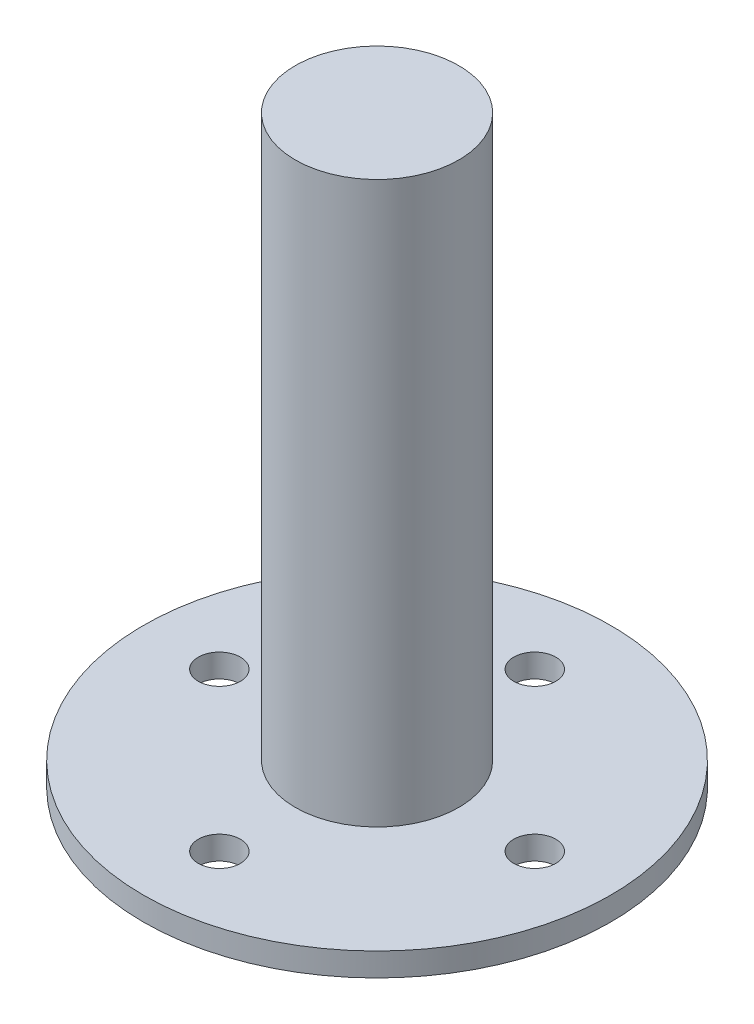
SolidWorks part; units mm, degrees
ref_plane "Płaszczyzna przednia" through (0, 0, 0) normal (0, 0, 1) x (1, 0, 0)
ref_plane "Płaszczyzna górna" through (0, 0, 0) normal (0, 1, 0) x (1, 0, 0)
ref_plane "Płaszczyzna prawa" through (0, 0, 0) normal (1, 0, 0) x (0, 0, -1)
sketch "Szkic1" plane through (0, 0, 0) normal (0, 1, 0) x (1, 0, 0)
  circle A0 centre (0, 0) radius 50
  dimension "D1" = 100
extrude "Dodanie-wyciągnięcie1" add sketch "Szkic1" along normal blind 5
sketch "Szkic2" plane through (0, 5, 0) normal (0, 1, 0) x (1, 0, 0)
  circle A0 centre (0, 0) radius 17.5
  dimension "D1" = 35
extrude "Dodanie-wyciągnięcie2" add sketch "Szkic2" along normal blind 120
sketch "Szkic5" plane through (0, 5, 0) normal (0, 1, 0) x (1, 0, 0)
  line L0 (0, 70.487) -> (0, -82.5361) construction
  line L1 (-92.2959, 0) -> (98.5614, 0) construction
  line L2 (0, 0) -> (-108.901, 0) construction
  circle A0 centre (0, 0) radius 33.75 construction
  circle A1 centre (-33.75, 0) radius 4
  circle A2 centre (0, 33.75) radius 4
  circle A3 centre (33.75, 0) radius 4
  circle A4 centre (0, -33.75) radius 4
  point P10 (0, 0)
  point P19 (0, 0)
  dimension "D2" = 67.5
  dimension "D3" = 8
  dimension "D1" = 0
  dimension "D4" = 4
hole_wizard "Otwór pod śrubę M81" positions "Szkic6" profile "Szkic8" hole size "M8" standard "ISO" end condition through all
sketch "Szkic6" plane through (0, 5, 0) normal (0, 1, 0) x (1, 0, 0)
  point P0 (-33.75, 0)
  point P3 (0, 33.75)
  point P7 (0, -33.75)
  point P10 (33.75, 0)
sketch "Szkic8" plane through (-33.75, 5, 0) normal (1, 0, 0) x (0, 0, 1)
  line L0 (0, 0) -> (0, 5)
  line L1 (0, 5) -> (4.5, 5)
  line L2 (4.5, 5) -> (4.5, 0)
  line L5 (4.5, 0) -> (0, 0)
  line L11 (0, -6.35) -> (0, 107.95) construction
  dimension "Średnica otworu na wylot" = 9
  dimension "Głębokość otworu na wylot" = 5
